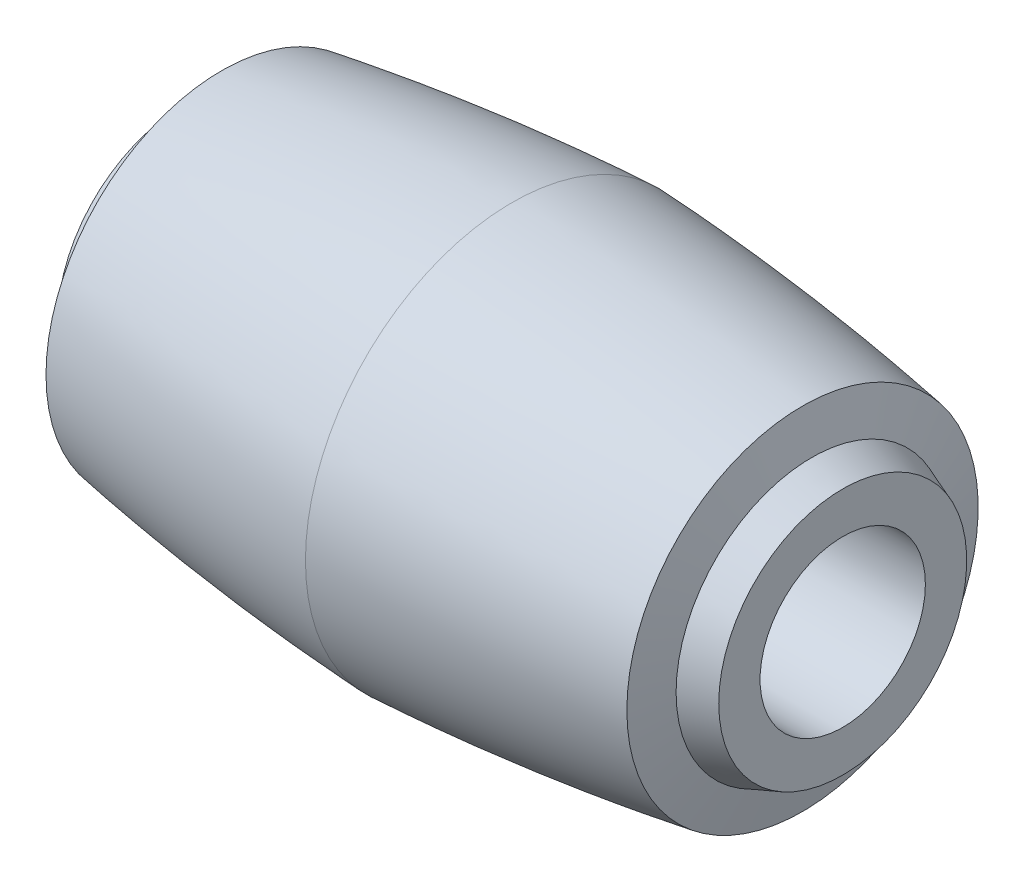
SolidWorks part; units mm, degrees
material "Silicon Rubber"
ref_plane "Front Plane" through (0, 0, 0) normal (0, 0, 1) x (1, 0, 0)
ref_plane "Top Plane" through (0, 0, 0) normal (0, 1, 0) x (1, 0, 0)
ref_plane "Right Plane" through (0, 0, 0) normal (1, 0, 0) x (0, 0, -1)
sketch "Sketch3" plane through (0, 0, 0) normal (0, 0, 1) x (1, 0, 0)
  line L0 (0, 10) -> (0, -10) construction
  line L1 (0, 0) -> (16, 0) construction
  line L2 (16, 0) -> (16, 6)
  line L3 (16, 6) -> (14.5, 6.5639)
  line L4 (14.5, 6.5639) -> (14.0542, 8.5)
  line L5 (0, 10) -> (0, 0)
  line L6 (0, 0) -> (16, 0)
  spline S0 degree 2 poles (0, 10) (7.0775, 9.6498) (14.0542, 8.5) knots 0 0 0 1 1 1
  dimension "D1" = 20
  dimension "D2" = 16
  dimension "D3" = 6
  dimension "D4" = 1.5
  dimension "D5" = 8.5
revolve "Revolve1" add sketch "Sketch3" angle 360 about L6
mirror "Mirror1" about plane through (0, 10, 0) normal (1, 0, 0) of "Revolve1"
sketch "Sketch7" plane through (16, 0, 0) normal (1, 0, 0) x (0, 0, -1)
  circle A0 centre (0, 0) radius 4
  dimension "D1" = 8
extrude "Cut-Extrude1" cut sketch "Sketch7" against normal through all
